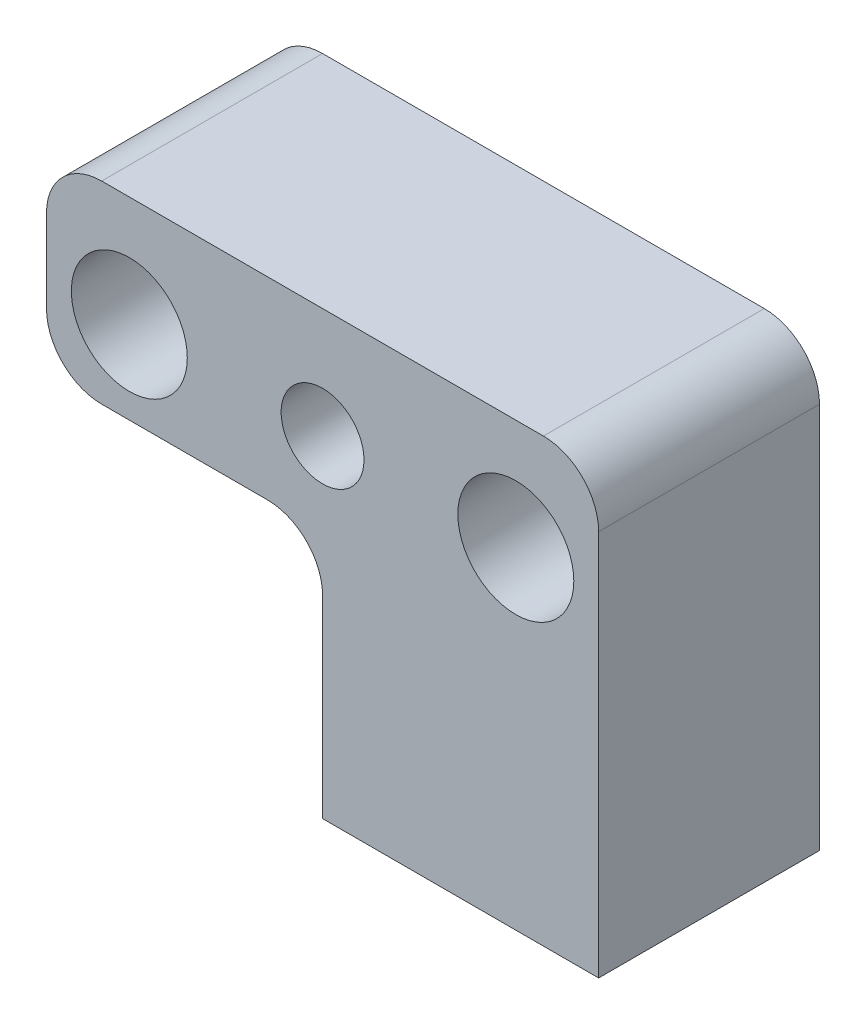
SolidWorks part; units mm, degrees
ref_plane "Front Plane" through (0, 0, 0) normal (0, 0, 1) x (1, 0, 0)
ref_plane "Top Plane" through (0, 0, 0) normal (0, 1, 0) x (1, 0, 0)
ref_plane "Right Plane" through (0, 0, 0) normal (1, 0, 0) x (0, 0, -1)
sketch "Sketch1" plane through (0, 0, 0) normal (0, 0, 1) x (1, 0, 0)
  line L1 (50, -40) -> (-50, -40)
  line L2 (50, -40) -> (50, 40)
  line L3 (50, 40) -> (-50, 40)
  line L4 (-50, -40) -> (-50, 40)
  line L5 (50, -40) -> (-50, 40) construction
  line L6 (50, 40) -> (-50, -40) construction
  point P0 (0, 0)
  dimension "D1" = 100
  dimension "D2" = 80
extrude "Boss-Extrude1" add sketch "Sketch1" along normal blind 40
sketch "Sketch2" plane through (0, 0, 40) normal (0, 0, 1) x (1, 0, 0)
  line L0 (-50, 0) -> (0, 0) construction
  line L1 (-50, 40) -> (-50, -40) construction
  line L2 (0, 0) -> (0, 40) construction
  line L3 (50, 40) -> (-50, 40) construction
  circle A0 centre (0, 0) radius 7.5
  circle A1 centre (-35, 0) radius 10.5
  circle A2 centre (35, 0) radius 10.5
  dimension "D1" = 21
  dimension "D3" = 15
  dimension "D2" = 15
extrude "Cut-Extrude1" cut sketch "Sketch2" against normal up to next
sketch "Sketch3" plane through (0, 0, 40) normal (0, 0, 1) x (1, 0, 0)
  line L0 (50, -40) -> (50, 40) construction
  line L1 (-50, 40) -> (50, 40)
  line L2 (-50, 40) -> (-50, 20)
  line L3 (-50, 20) -> (50, 20)
  line L4 (50, 40) -> (50, 20)
  dimension "D1" = 20
extrude "Cut-Extrude2" cut sketch "Sketch3" against normal up to next
sketch "Sketch4" plane through (0, -40, 0) normal (0, -1, 0) x (1, 0, 0)
  line L0 (-50, 20) -> (-38.6852, 20) construction
  line L1 (-50, 40) -> (-50, 0) construction
  line L2 (50, 40) -> (50, 0) construction
  line L3 (0, 0) -> (0, 40) construction
  line L4 (-50, 40) -> (50, 40) construction
  line L5 (-33.3148, 20) -> (-18.6852, 20) construction
  line L6 (-13.3148, 20) -> (50, 20) construction
  circle A2 centre (16, 20) radius 3
  circle A3 centre (36, 20) radius 3
  dimension "D3" = 6
  dimension "D4" = 6
  dimension "D1" = 34
  dimension "D2" = 14
sketch "Sketch5" plane through (0, 0, 0) normal (0, 0, -1) x (-1, 0, 0)
  line L1 (50, -40) -> (0, -40)
  line L2 (50, -40) -> (50, -15)
  line L3 (50, -15) -> (0, -15)
  line L4 (0, -40) -> (0, -15)
  dimension "D1" = 50
  dimension "D2" = 25
extrude "Cut-Extrude4" cut sketch "Sketch5" against normal up to next
fillet "Fillet1" radius 10 1 edges at (0, -15, 20)
fillet "Fillet2" radius 10 1 edges at (-50, -15, 20)
fillet "Fillet3" radius 10 1 edges at (-50, 20, 20)
fillet "Fillet4" radius 10 1 edges at (50, 20, 20)
sketch "Sketch6" plane through (0, -40, 0) normal (0, -1, 0) x (1, 0, 0)
  line L1 (0, 40) -> (50, 40)
  line L2 (0, 40) -> (0, 0)
  line L3 (0, 0) -> (50, 0)
  line L4 (50, 40) -> (50, 0)
extrude "Boss-Extrude2" add sketch "Sketch6" along normal blind 20
extrude "Cut-Extrude5" cut sketch "Sketch4" against normal mid plane 40
